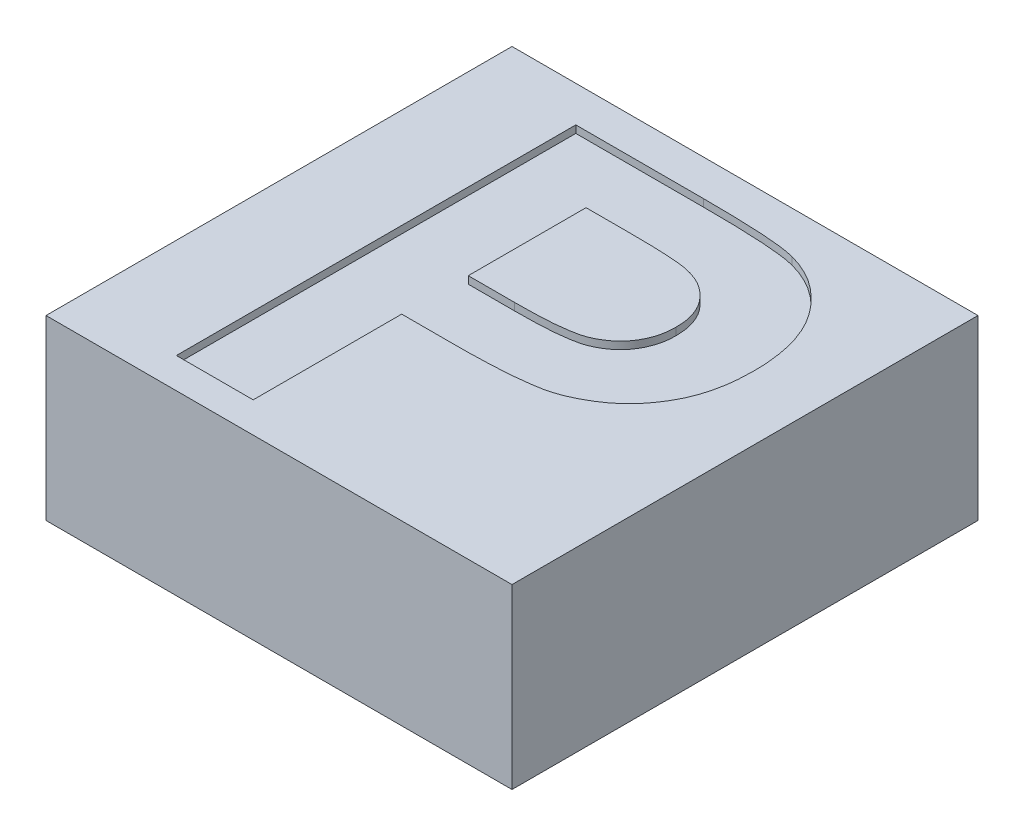
SolidWorks part; units mm, degrees
ref_plane "Front Plane" through (0, 0, 0) normal (0, 0, 1) x (1, 0, 0)
ref_plane "Top Plane" through (0, 0, 0) normal (0, 1, 0) x (1, 0, 0)
ref_plane "Right Plane" through (0, 0, 0) normal (1, 0, 0) x (0, 0, -1)
sketch "Sketch1" plane through (0, 0, 0) normal (0, 1, 0) x (1, 0, 0)
  line L1 (0, 0) -> (31.5, 0)
  line L2 (0, 0) -> (0, 31.5)
  line L3 (0, 31.5) -> (31.5, 31.5)
  line L4 (31.5, 0) -> (31.5, 31.5)
  dimension "D1" = 31.5
  dimension "D2" = 31.5
extrude "Boss-Extrude1" add sketch "Sketch1" along normal blind 12
sketch "Sketch2" plane through (0, 12, 0) normal (0, 1, 0) x (1, 0, 0)
  line L0 (0, 15.75) -> (31.5, 15.75) construction
  line L1 (0, 31.5) -> (0, 0) construction
  line L2 (31.5, 0) -> (31.5, 31.5) construction
  line L3 (15.75, 31.5) -> (15.75, 0) construction
  line L4 (31.5, 31.5) -> (0, 31.5) construction
  line L5 (0, 0) -> (31.5, 0) construction
  text T0 "<b>P</b>" font "Arial" height 27
  point P13 (0, 0)
  point P14 (12.723, 12.7861)
  point P15 (15.75, 15.75)
  point P16 (15.75, 15.75)
  point P17 (20.4586, 8.2036)
  point P18 (5.66, 14.3837)
extrude "Cut-Extrude1" cut sketch "Sketch2" against normal blind 0.5
